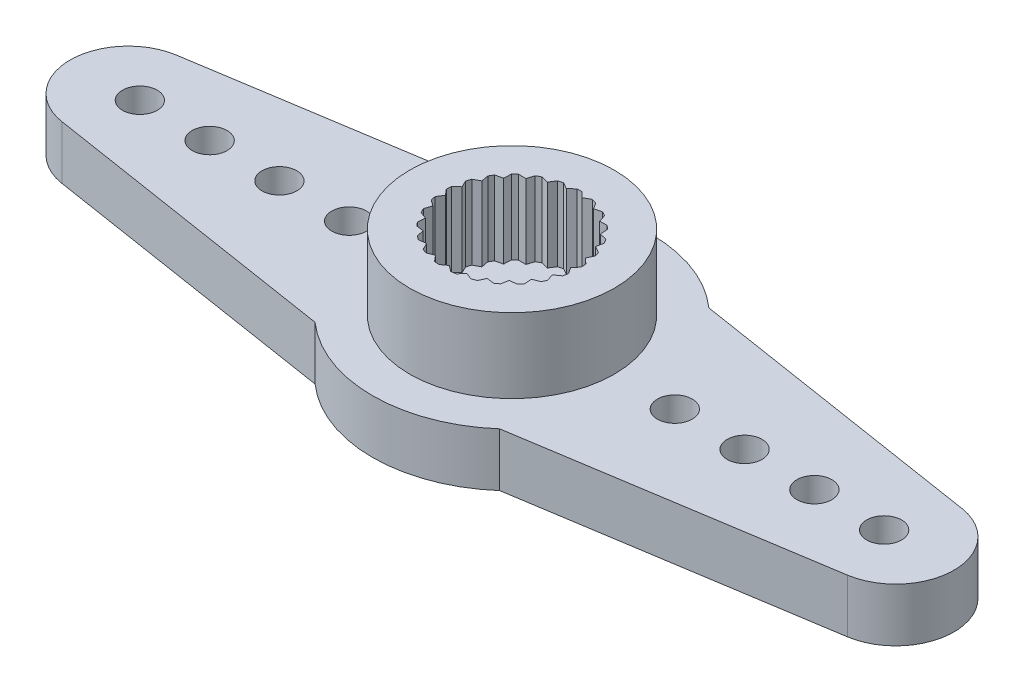
SolidWorks part; units mm, degrees
material "ABS"
ref_plane "Front Plane" through (0, 0, 0) normal (0, 0, 1) x (1, 0, 0)
ref_plane "Top Plane" through (0, 0, 0) normal (0, 1, 0) x (1, 0, 0)
ref_plane "Right Plane" through (0, 0, 0) normal (1, 0, 0) x (0, 0, -1)
sketch "Sketch2" plane through (0, 0, 0) normal (0, 1, 0) x (1, 0, 0)
  circle A0 centre (0, 0) radius 6
  circle A1 centre (0, 0) radius 1.5
  dimension "D1" = 12
  dimension "D2" = 3
extrude "Boss-Extrude1" add sketch "Sketch2" along normal mid plane 2.3
sketch "Sketch3" plane through (0, 1.15, 0) normal (0, 1, 0) x (1, 0, 0)
  line L0 (0, 0) -> (0, 2.9) construction
  line L3 (0, 0) -> (0.376, 2.9763) construction
  line L52 (0.1074, 2.898) -> (0.3384, 2.6787)
  line L53 (-0.1074, 2.898) -> (-0.3384, 2.6787)
  line L54 (0.8248, 2.7802) -> (0.9939, 2.5104)
  line L55 (0.6167, 2.8337) -> (0.3384, 2.6787)
  line L56 (1.4903, 2.4878) -> (1.587, 2.1843)
  line L57 (1.302, 2.5913) -> (0.9939, 2.5104)
  line L58 (2.0621, 2.039) -> (2.0804, 1.721)
  line L59 (1.9055, 2.1861) -> (1.587, 2.1843)
  line L60 (2.5044, 1.4621) -> (2.443, 1.1496)
  line L61 (2.3893, 1.6435) -> (2.0804, 1.721)
  line L62 (2.7894, 0.7934) -> (2.6522, 0.5059)
  line L63 (2.723, 0.9977) -> (2.443, 1.1496)
  line L64 (2.899, 0.0748) -> (2.6947, -0.1695)
  line L65 (2.8855, 0.2892) -> (2.6522, 0.5059)
  line L66 (2.8265, -0.6486) -> (2.5679, -0.8343)
  line L67 (2.8668, -0.4375) -> (2.6947, -0.1695)
  line L68 (2.5765, -1.3311) -> (2.2797, -1.4467)
  line L69 (2.6679, -1.1367) -> (2.5679, -0.8343)
  line L70 (2.1645, -1.93) -> (1.8483, -1.9682)
  line L71 (2.3014, -1.7645) -> (2.2797, -1.4467)
  line L72 (1.6165, -2.4077) -> (1.3007, -2.366)
  line L73 (1.7903, -2.2814) -> (1.8483, -1.9682)
  line L74 (0.967, -2.734) -> (0.6715, -2.6152)
  line L75 (1.1667, -2.655) -> (1.3007, -2.366)
  line L76 (0.2566, -2.8886) -> (0, -2.7)
  line L77 (0.4698, -2.8617) -> (0.6715, -2.6152)
  line L78 (-0.4698, -2.8617) -> (-0.6715, -2.6152)
  line L79 (-0.2566, -2.8886) -> (0, -2.7)
  line L80 (-1.1667, -2.655) -> (-1.3007, -2.366)
  line L81 (-0.967, -2.734) -> (-0.6715, -2.6152)
  line L82 (-1.7903, -2.2814) -> (-1.8483, -1.9682)
  line L83 (-1.6165, -2.4077) -> (-1.3007, -2.366)
  line L84 (-2.3014, -1.7645) -> (-2.2797, -1.4467)
  line L85 (-2.1645, -1.93) -> (-1.8483, -1.9682)
  line L86 (-2.6679, -1.1367) -> (-2.5679, -0.8343)
  line L87 (-2.5765, -1.3311) -> (-2.2797, -1.4467)
  line L88 (-2.8668, -0.4375) -> (-2.6947, -0.1695)
  line L89 (-2.8265, -0.6486) -> (-2.5679, -0.8343)
  line L90 (-2.8855, 0.2892) -> (-2.6522, 0.5059)
  line L91 (-2.899, 0.0748) -> (-2.6947, -0.1695)
  line L92 (-2.723, 0.9977) -> (-2.443, 1.1496)
  line L93 (-2.7894, 0.7934) -> (-2.6522, 0.5059)
  line L94 (-2.3893, 1.6435) -> (-2.0804, 1.721)
  line L95 (-2.5044, 1.4621) -> (-2.443, 1.1496)
  line L96 (-1.9055, 2.1861) -> (-1.587, 2.1843)
  line L97 (-2.0621, 2.039) -> (-2.0804, 1.721)
  line L98 (-1.302, 2.5913) -> (-0.9939, 2.5104)
  line L99 (-1.4903, 2.4878) -> (-1.587, 2.1843)
  line L100 (-0.6167, 2.8337) -> (-0.3384, 2.6787)
  line L101 (-0.8248, 2.7802) -> (-0.9939, 2.5104)
  line L102 (-2.533, 1.6075) -> (-2.3893, 1.6435) construction
  line L103 (-2.533, 1.6075) -> (-2.5044, 1.4621) construction
  line L104 (-2.8532, 0.9271) -> (-2.723, 0.9977) construction
  line L105 (-2.8532, 0.9271) -> (-2.7894, 0.7934) construction
  line L106 (-2.9941, 0.1884) -> (-2.8855, 0.2892) construction
  line L107 (-2.9941, 0.1884) -> (-2.899, 0.0748) construction
  line L108 (-2.9469, -0.5621) -> (-2.8668, -0.4375) construction
  line L109 (-2.9469, -0.5621) -> (-2.8265, -0.6486) construction
  line L110 (0, 3) -> (0.1074, 2.898) construction
  line L111 (0, 2.9) -> (0, 3) construction
  line L112 (0, 3) -> (-0.1074, 2.898) construction
  line L113 (-0.7461, 2.9057) -> (-0.6167, 2.8337) construction
  line L114 (-0.7461, 2.9057) -> (-0.8248, 2.7802) construction
  line L115 (-1.4453, 2.6289) -> (-1.302, 2.5913) construction
  line L116 (-1.4453, 2.6289) -> (-1.4903, 2.4878) construction
  line L117 (-2.0536, 2.1869) -> (-1.9055, 2.1861) construction
  line L118 (-2.0536, 2.1869) -> (-2.0621, 2.039) construction
  line L119 (-2.7145, -1.2773) -> (-2.6679, -1.1367) construction
  line L120 (-2.7145, -1.2773) -> (-2.5765, -1.3311) construction
  line L121 (-2.3115, -1.9123) -> (-2.3014, -1.7645) construction
  line L122 (-2.3115, -1.9123) -> (-2.1645, -1.93) construction
  line L123 (-1.7634, -2.4271) -> (-1.7903, -2.2814) construction
  line L124 (-1.7634, -2.4271) -> (-1.6165, -2.4077) construction
  line L125 (-1.1044, -2.7893) -> (-1.1667, -2.655) construction
  line L126 (-1.1044, -2.7893) -> (-0.967, -2.734) construction
  line L127 (-0.376, -2.9763) -> (-0.4698, -2.8617) construction
  line L128 (-0.376, -2.9763) -> (-0.2566, -2.8886) construction
  line L129 (0.376, -2.9763) -> (0.2566, -2.8886) construction
  line L130 (0.376, -2.9763) -> (0.4698, -2.8617) construction
  line L131 (1.1044, -2.7893) -> (0.967, -2.734) construction
  line L132 (1.1044, -2.7893) -> (1.1667, -2.655) construction
  line L133 (1.7634, -2.4271) -> (1.6165, -2.4077) construction
  line L134 (1.7634, -2.4271) -> (1.7903, -2.2814) construction
  line L135 (2.3115, -1.9123) -> (2.3014, -1.7645) construction
  line L136 (2.3115, -1.9123) -> (2.1645, -1.93) construction
  line L137 (2.7145, -1.2773) -> (2.6679, -1.1367) construction
  line L138 (2.7145, -1.2773) -> (2.5765, -1.3311) construction
  line L139 (2.9469, -0.5621) -> (2.8668, -0.4375) construction
  line L140 (2.9469, -0.5621) -> (2.8265, -0.6486) construction
  line L141 (2.9941, 0.1884) -> (2.8855, 0.2892) construction
  line L142 (2.9941, 0.1884) -> (2.899, 0.0748) construction
  line L143 (2.8532, 0.9271) -> (2.723, 0.9977) construction
  line L144 (2.8532, 0.9271) -> (2.7894, 0.7934) construction
  line L145 (2.533, 1.6075) -> (2.3893, 1.6435) construction
  line L146 (2.533, 1.6075) -> (2.5044, 1.4621) construction
  line L147 (2.0536, 2.1869) -> (1.9055, 2.1861) construction
  line L148 (2.0536, 2.1869) -> (2.0621, 2.039) construction
  line L149 (1.4453, 2.6289) -> (1.302, 2.5913) construction
  line L150 (1.4453, 2.6289) -> (1.4903, 2.4878) construction
  line L151 (0.7461, 2.9057) -> (0.6167, 2.8337) construction
  line L152 (0.7461, 2.9057) -> (0.8248, 2.7802) construction
  circle A0 centre (0, 0) radius 4.4
  circle A1 centre (0, 0) radius 3 construction
  circle A2 centre (0, 0) radius 2.7 construction
  arc A3 (-0.6167, 2.8337) -> (-0.8248, 2.7802) centre (0, 0) ccw
  arc A4 (-0.1074, 2.898) -> (-0.6167, 2.8337) centre (0, 0) ccw construction
  arc A5 (-0.8248, 2.7802) -> (-1.302, 2.5913) centre (0, 0) ccw construction
  arc A6 (-1.302, 2.5913) -> (-1.4903, 2.4878) centre (0, 0) ccw
  arc A7 (-1.4903, 2.4878) -> (-1.9055, 2.1861) centre (0, 0) ccw construction
  arc A8 (-1.9055, 2.1861) -> (-2.0621, 2.039) centre (0, 0) ccw
  arc A9 (-2.0621, 2.039) -> (-2.3893, 1.6435) centre (0, 0) ccw construction
  arc A10 (-2.3893, 1.6435) -> (-2.5044, 1.4621) centre (0, 0) ccw
  arc A11 (-2.5044, 1.4621) -> (-2.723, 0.9977) centre (0, 0) ccw construction
  arc A12 (-2.723, 0.9977) -> (-2.7894, 0.7934) centre (0, 0) ccw
  arc A13 (-2.7894, 0.7934) -> (-2.8855, 0.2892) centre (0, 0) ccw construction
  arc A14 (-2.8855, 0.2892) -> (-2.899, 0.0748) centre (0, 0) ccw
  arc A15 (-2.899, 0.0748) -> (-2.8668, -0.4375) centre (0, 0) ccw construction
  arc A16 (-2.8668, -0.4375) -> (-2.8265, -0.6486) centre (0, 0) ccw
  arc A17 (-2.8265, -0.6486) -> (-2.6679, -1.1367) centre (0, 0) ccw construction
  arc A18 (-2.6679, -1.1367) -> (-2.5765, -1.3311) centre (0, 0) ccw
  arc A19 (-2.5765, -1.3311) -> (-2.3014, -1.7645) centre (0, 0) ccw construction
  arc A20 (-2.3014, -1.7645) -> (-2.1645, -1.93) centre (0, 0) ccw
  arc A21 (-2.1645, -1.93) -> (-1.7903, -2.2814) centre (0, 0) ccw construction
  arc A22 (-1.7903, -2.2814) -> (-1.6165, -2.4077) centre (0, 0) ccw
  arc A23 (-1.6165, -2.4077) -> (-1.1667, -2.655) centre (0, 0) ccw construction
  arc A24 (-1.1667, -2.655) -> (-0.967, -2.734) centre (0, 0) ccw
  arc A25 (-0.967, -2.734) -> (-0.4698, -2.8617) centre (0, 0) ccw construction
  arc A26 (-0.4698, -2.8617) -> (-0.2566, -2.8886) centre (0, 0) ccw
  arc A27 (-0.2566, -2.8886) -> (0.2566, -2.8886) centre (0, 0) ccw construction
  arc A28 (0.2566, -2.8886) -> (0.4698, -2.8617) centre (0, 0) ccw
  arc A29 (0.4698, -2.8617) -> (0.967, -2.734) centre (0, 0) ccw construction
  arc A30 (0.967, -2.734) -> (1.1667, -2.655) centre (0, 0) ccw
  arc A31 (1.1667, -2.655) -> (1.6165, -2.4077) centre (0, 0) ccw construction
  arc A32 (1.6165, -2.4077) -> (1.7903, -2.2814) centre (0, 0) ccw
  arc A33 (1.7903, -2.2814) -> (2.1645, -1.93) centre (0, 0) ccw construction
  arc A34 (2.1645, -1.93) -> (2.3014, -1.7645) centre (0, 0) ccw
  arc A35 (2.3014, -1.7645) -> (2.5765, -1.3311) centre (0, 0) ccw construction
  arc A36 (2.5765, -1.3311) -> (2.6679, -1.1367) centre (0, 0) ccw
  arc A37 (2.6679, -1.1367) -> (2.8265, -0.6486) centre (0, 0) ccw construction
  arc A38 (2.8265, -0.6486) -> (2.8668, -0.4375) centre (0, 0) ccw
  arc A39 (2.8668, -0.4375) -> (2.899, 0.0748) centre (0, 0) ccw construction
  arc A40 (2.899, 0.0748) -> (2.8855, 0.2892) centre (0, 0) ccw
  arc A41 (2.8855, 0.2892) -> (2.7894, 0.7934) centre (0, 0) ccw construction
  arc A42 (2.7894, 0.7934) -> (2.723, 0.9977) centre (0, 0) ccw
  arc A43 (2.723, 0.9977) -> (2.5044, 1.4621) centre (0, 0) ccw construction
  arc A44 (2.5044, 1.4621) -> (2.3893, 1.6435) centre (0, 0) ccw
  arc A45 (2.3893, 1.6435) -> (2.0621, 2.039) centre (0, 0) ccw construction
  arc A46 (2.0621, 2.039) -> (1.9055, 2.1861) centre (0, 0) ccw
  arc A47 (1.9055, 2.1861) -> (1.4903, 2.4878) centre (0, 0) ccw construction
  arc A48 (1.4903, 2.4878) -> (1.302, 2.5913) centre (0, 0) ccw
  arc A49 (1.302, 2.5913) -> (0.8248, 2.7802) centre (0, 0) ccw construction
  arc A50 (0.8248, 2.7802) -> (0.6167, 2.8337) centre (0, 0) ccw
  arc A51 (0.3635, 2.8771) -> (0.1074, 2.898) centre (0, 0) ccw construction
  arc A52 (0.1074, 2.898) -> (-0.1074, 2.898) centre (0, 0) ccw
  arc A53 (0.6167, 2.8337) -> (0.3635, 2.8771) centre (0, 0) ccw construction
  point P84 (0, 0)
  dimension "D1" = 8.8
  dimension "D2" = 5.4
  dimension "D3" = 6
  dimension "D6" = 5.8
  dimension "D4" = 7.2
  dimension "D5" = 25
extrude "Boss-Extrude2" add sketch "Sketch3" along normal blind 3.2
sketch "Sketch4" plane through (0, 0, 0) normal (0, 1, 0) x (1, 0, 0)
  line L0 (0, 0) -> (16, 0) construction
  line L1 (3.9686, 4.5) -> (16.8881, 2.4697)
  line L2 (3.9686, -4.5) -> (16.8881, -2.4697)
  line L3 (16, 0) -> (13, 0) construction
  circle A0 centre (0, 0) radius 6 construction
  arc A1 (3.9686, -4.5) -> (3.9686, 4.5) centre (0, 0) ccw
  arc A2 (16.8881, 2.4697) -> (16.8881, -2.4697) centre (16.5, 0) cw
  circle A3 centre (16, 0) radius 0.75
  circle A4 centre (13, 0) radius 0.75
  circle A5 centre (10, 0) radius 0.75
  circle A6 centre (7, 0) radius 0.75
  dimension "D3" = 2.5
  dimension "D5" = 1.5
  dimension "D2" = 9
  dimension "D7" = 3
  dimension "D4" = 0.5
  dimension "D1" = 16
  dimension "D6" = 4
extrude "Boss-Extrude3" add sketch "Sketch4" along normal mid plane 2.3
pattern_circular "CirPattern1" count 2 over 360 about axis through (0, 0, 0) along (0, 1, 0) of "Boss-Extrude3"
sketch "Sketch5" [suppressed] plane through (0, 0, 0) normal (0, 1, 0) x (1, 0, 0)
  line L0 (3, 7) -> (-3, 7) construction
  circle A0 centre (0, 0) radius 10
  circle A1 centre (0, 7) radius 0.75
  circle A2 centre (-3, 7) radius 0.75
  circle A3 centre (3, 7) radius 0.75
  circle A4 centre (7, 3) radius 0.75
  circle A5 centre (7, 0) radius 0.75
  circle A6 centre (7, -3) radius 0.75
  circle A7 centre (3, -7) radius 0.75
  circle A8 centre (0, -7) radius 0.75
  circle A9 centre (-3, -7) radius 0.75
  circle A10 centre (-7, -3) radius 0.75
  circle A11 centre (-7, 0) radius 0.75
  circle A12 centre (-7, 3) radius 0.75
  circle A13 centre (0, 0) radius 1.5 construction
  circle A14 centre (0, 0) radius 1.5
  point P8 (0, 7)
  point P31 (0, 0)
  dimension "D1" = 1.5
  dimension "D3" = 2.25
  dimension "D4" = 6
  dimension "D2" = 7
  dimension "D5" = 4
extrude "Boss-Extrude4" [suppressed] add sketch "Sketch5" along normal mid plane 2.3
sketch "Sketch6" plane through (0, 1.15, 0) normal (0, 1, 0) x (1, 0, 0)
  line L0 (-16.8881, 2.4697) -> (-3.9686, 4.5)
  line L1 (-16.8881, -2.4697) -> (-3.9686, -4.5)
  line L2 (3.9686, 4.5) -> (16.8881, 2.4697)
  line L3 (16.8881, -2.4697) -> (3.9686, -4.5)
  arc A0 (-16.8881, 2.4697) -> (-16.8881, -2.4697) centre (-16.5, 0) ccw
  arc A1 (-3.9686, 4.5) -> (3.9686, 4.5) centre (0, 0) cw
  arc A2 (-3.9686, -4.5) -> (3.9686, -4.5) centre (0, 0) ccw
  arc A3 (16.8881, -2.4697) -> (16.8881, 2.4697) centre (16.5, 0) ccw
equation "\"N_hole\"= 4"
equation "\"N_horn\" = 2"
equation "\"D6@Sketch4\"=\"N_hole\""
equation "\"D1@CirPattern1\"=\"N_horn\""
equation "\"D1@Sketch4\"=(\"N_hole\" - 1) *3 +7"
